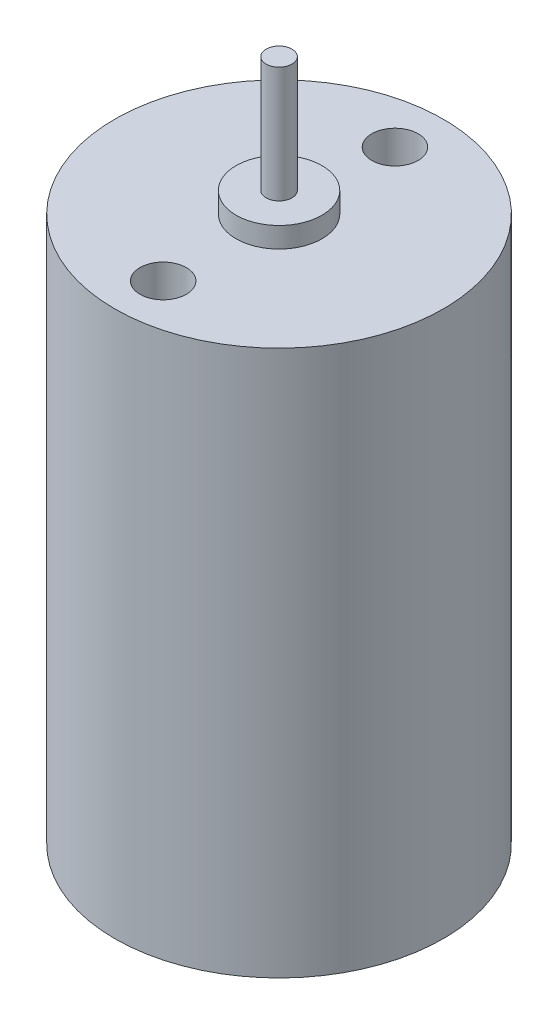
SolidWorks part; units mm, degrees
ref_plane "Front Plane" through (0, 0, 0) normal (0, 0, 1) x (1, 0, 0)
ref_plane "Top Plane" through (0, 0, 0) normal (0, 1, 0) x (1, 0, 0)
ref_plane "Right Plane" through (0, 0, 0) normal (1, 0, 0) x (0, 0, -1)
other "Center of Mass"
sketch "Sketch1" plane through (0, 0, 0) normal (0, 1, 0) x (1, 0, 0)
  circle A0 centre (0, 0) radius 12.05
extrude "Boss-Extrude1" add sketch "Sketch1" along normal blind 40
sketch "Sketch2" plane through (0, 40, 0) normal (0, 1, 0) x (1, 0, 0)
  circle A0 centre (0, 0) radius 3.15
extrude "Boss-Extrude2" add sketch "Sketch2" along normal blind 1.5
sketch "Sketch3" plane through (0, 41.5, 0) normal (0, 1, 0) x (1, 0, 0)
  circle A0 centre (0, 0) radius 0.95
extrude "Boss-Extrude3" add sketch "Sketch3" along normal blind 8.5
sketch "Sketch4" plane through (0, 40, 0) normal (0, 1, 0) x (1, 0, 0)
  circle A0 centre (0, 8.5) radius 1.7
  circle A1 centre (0, -8.5) radius 1.7
  circle A2 centre (0, 0) radius 12.05 construction
  dimension "D3" = 3.4
  dimension "D4" = 3.4
  dimension "D1" = 17
  dimension "D2" = 8.5
extrude "Cut-Extrude1" cut sketch "Sketch4" against normal blind 5
